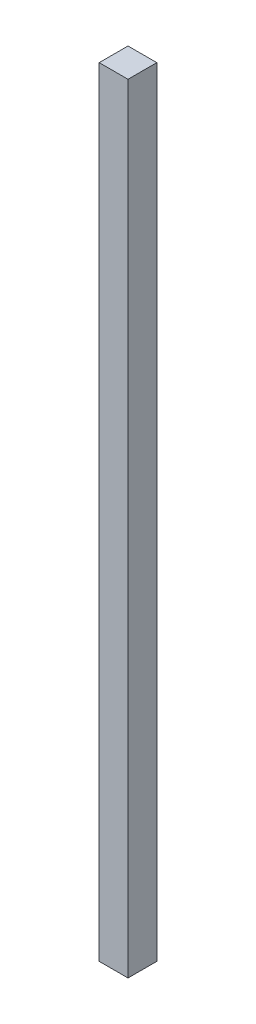
SolidWorks part; units mm, degrees
ref_plane "Front Plane" through (0, 0, 0) normal (0, 0, 1) x (1, 0, 0)
ref_plane "Top Plane" through (0, 0, 0) normal (0, 1, 0) x (1, 0, 0)
ref_plane "Right Plane" through (0, 0, 0) normal (1, 0, 0) x (0, 0, -1)
sketch "Sketch1" plane through (0, 0, 0) normal (0, 1, 0) x (1, 0, 0)
  line L1 (-44.45, -44.45) -> (44.45, -44.45)
  line L2 (-44.45, -44.45) -> (-44.45, 44.45)
  line L3 (-44.45, 44.45) -> (44.45, 44.45)
  line L4 (44.45, -44.45) -> (44.45, 44.45)
  line L5 (-44.45, -44.45) -> (44.45, 44.45) construction
  line L6 (-44.45, 44.45) -> (44.45, -44.45) construction
  point P0 (0, 0)
  dimension "D1" = 88.9
  dimension "D2" = 88.9
extrude "Boss-Extrude1" add sketch "Sketch1" along normal blind 2401.8875
hole_wizard "23/64 (0.35938) Diameter Hole1" positions "Sketch2" profile "Sketch3" hole size "23/64" standard "ANSI Inch"
sketch "Sketch2" plane through (44.45, 0, 0) normal (1, 0, 0) x (0, 0, -1)
  point P0 (0, 1085.85)
  point P2 (0, 1035.05)
  point P4 (0, 279.4)
  point P6 (0, 330.2)
sketch "Sketch3" plane through (44.45, 1085.85, 0) normal (0, 1, 0) x (0, 0, -1)
  line L0 (0, 0) -> (0, 88.9)
  line L1 (0, 88.9) -> (4.5641, 88.9)
  line L2 (4.5641, 88.9) -> (4.5641, 0)
  line L5 (4.5641, 0) -> (0, 0)
  line L11 (0, -6.35) -> (0, 107.95) construction
  dimension "Thru Hole Dia." = 9.1283
  dimension "Thru Hole Depth" = 88.9
hole_wizard "23/64 (0.35938) Diameter Hole2" positions "Sketch4" profile "Sketch5" hole size "23/64" standard "ANSI Inch"
sketch "Sketch4" plane through (-44.45, 0, 0) normal (-1, 0, 0) x (0, 0, 1)
  point P0 (0, 1316.0375)
  point P2 (0, 1366.8375)
sketch "Sketch5" plane through (-44.45, 1316.0375, 0) normal (0, 1, 0) x (0, 0, 1)
  line L0 (0, 0) -> (0, 88.9)
  line L1 (0, 88.9) -> (4.5641, 88.9)
  line L2 (4.5641, 88.9) -> (4.5641, 0)
  line L5 (4.5641, 0) -> (0, 0)
  line L11 (0, -6.35) -> (0, 107.95) construction
  dimension "Thru Hole Dia." = 9.1283
  dimension "Thru Hole Depth" = 88.9
